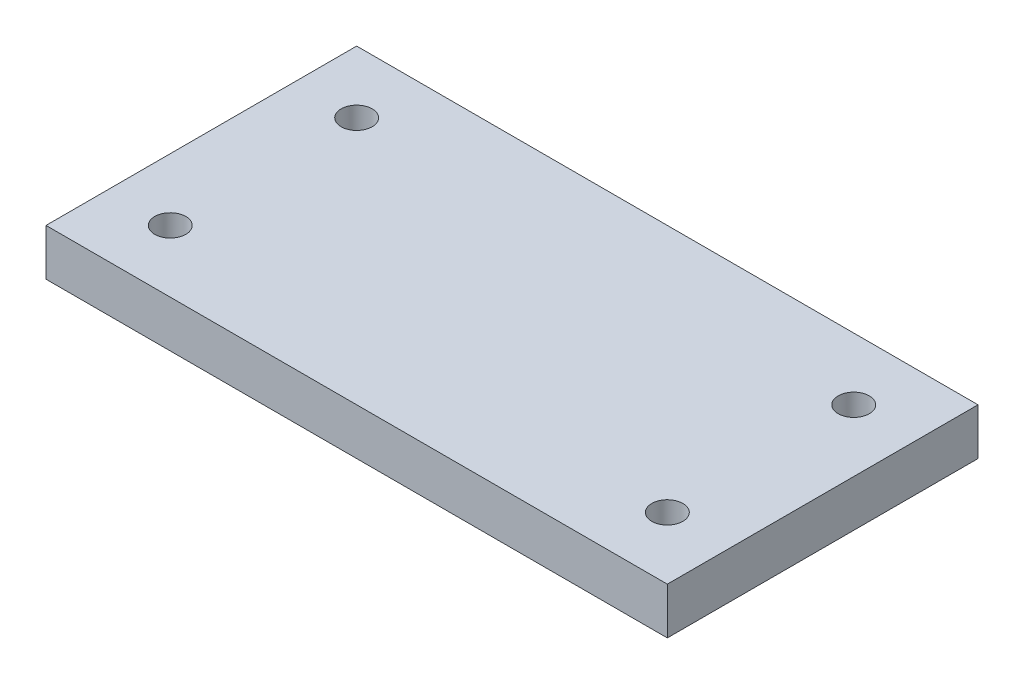
SolidWorks part; units mm, degrees
ref_plane "前视基准面" through (0, 0, 0) normal (0, 0, 1) x (1, 0, 0)
ref_plane "上视基准面" through (0, 0, 0) normal (0, 1, 0) x (1, 0, 0)
ref_plane "右视基准面" through (0, 0, 0) normal (1, 0, 0) x (0, 0, -1)
other "Configuration Table"
sketch "草图1" plane through (0, 0, 0) normal (0, 1, 0) x (1, 0, 0)
  line L1 (-100, -50) -> (100, -50)
  line L2 (-100, -50) -> (-100, 50)
  line L3 (-100, 50) -> (100, 50)
  line L4 (100, -50) -> (100, 50)
  line L5 (0, 50) -> (0, -50) construction
  line L6 (-100, 0) -> (100, 0) construction
  point P0 (0, 0)
extrude "凸台-拉伸1" add sketch "草图1" along normal blind 15
sketch "草图2" plane through (0, 0, 0) normal (0, 1, 0) x (1, 0, 0)
  circle A0 centre (-80, -30) radius 5
  circle A1 centre (80, -30) radius 5
  circle A2 centre (-80, 30) radius 5
extrude "切除-拉伸1" cut sketch "草图2" along normal blind 30
sketch "草图3" plane through (0, 0, 0) normal (0, 1, 0) x (1, 0, 0)
  circle A0 centre (80, 30) radius 5
extrude "切除-拉伸2" cut sketch "草图3" along normal blind 30
